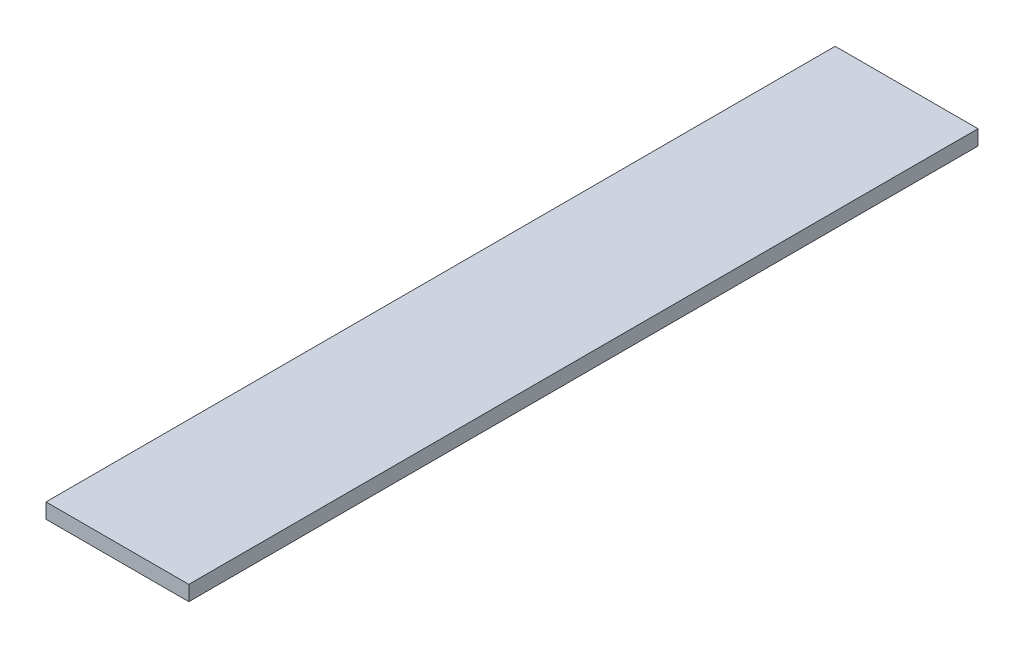
SolidWorks part; units mm, degrees
ref_plane "Front Plane" through (0, 0, 0) normal (0, 0, 1) x (1, 0, 0)
ref_plane "Top Plane" through (0, 0, 0) normal (0, 1, 0) x (1, 0, 0)
ref_plane "Right Plane" through (0, 0, 0) normal (1, 0, 0) x (0, 0, -1)
sketch "Sketch2" plane through (0, 0, 0) normal (0, 0, 1) x (1, 0, 0)
  line L1 (-26.8287, 14.0494) -> (-2.6987, 14.0494)
  line L2 (-26.8287, 14.0494) -> (-26.8287, 11.5094)
  line L3 (-26.8287, 11.5094) -> (-2.6987, 11.5094)
  line L4 (-2.6987, 14.0494) -> (-2.6987, 11.5094)
  dimension "D1" = 2.54
  dimension "D2" = 24.13
extrude "Boss-Extrude1" add sketch "Sketch2" along normal blind 133.35
